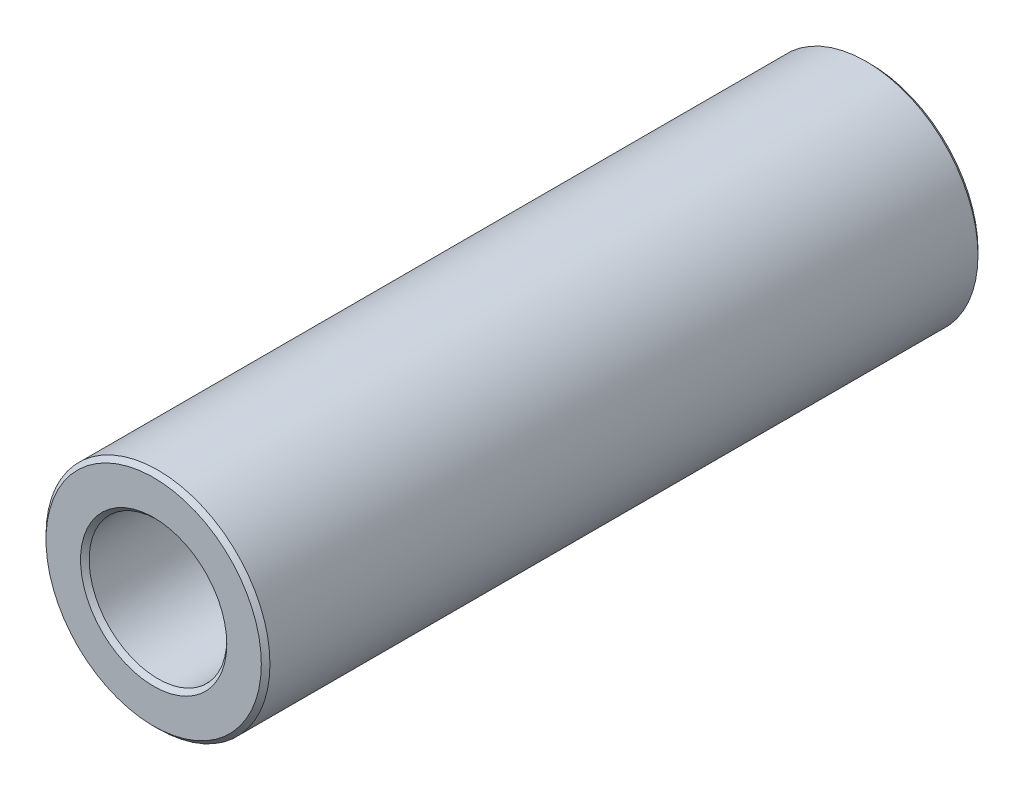
SolidWorks part; units mm, degrees
ref_plane "Front Plane" through (0, 0, 0) normal (0, 0, 1) x (1, 0, 0)
ref_plane "Top Plane" through (0, 0, 0) normal (0, 1, 0) x (1, 0, 0)
ref_plane "Right Plane" through (0, 0, 0) normal (1, 0, 0) x (0, 0, -1)
sketch "Sketch1" plane through (0, 0, 0) normal (0, 0, 1) x (1, 0, 0)
  circle A0 centre (0, 0) radius 3.9688 construction
  circle A1 centre (0, 0) radius 2.4384 construction
  point P4 (0, 3.9688)
  dimension "ID" = 4.8768
  dimension "OD" = 7.9375
sketch "Sketch2" plane through (0, 0, 0) normal (1, 0, 0) x (0, 0, -1)
  line L0 (-12.7, 3.9688) -> (12.7, 3.9688) construction
  dimension "Length" = 25.4
sketch "Sketch3" plane through (0, 0, 0) normal (0, 0, 1) x (1, 0, 0)
  circle A0 centre (0, 0) radius 2.4384 construction
  circle A1 centre (0, 0) radius 3.9688 construction
  circle A2 centre (0, 0) radius 2.4384
  circle A3 centre (0, 0) radius 3.9688
extrude "Boss-Extrude1" add sketch "Sketch3" against normal up to vertex (12.7 mm away) and the other way up to vertex (12.7 mm away) up to point (0, 3.9688, -12.7) other way up to point (0, 3.9688, 12.7)
chamfer "Chamfer1" distance 0.153 angle 45 4 edges at (3.9688, 0, 12.7) (3.9688, 0, -12.7) (2.4384, 0, 12.7) (2.4384, 0, -12.7)
equation "\"D1@Chamfer1\"=(\"OD@Sketch1\"-\"ID@Sketch1\")*0.05"
